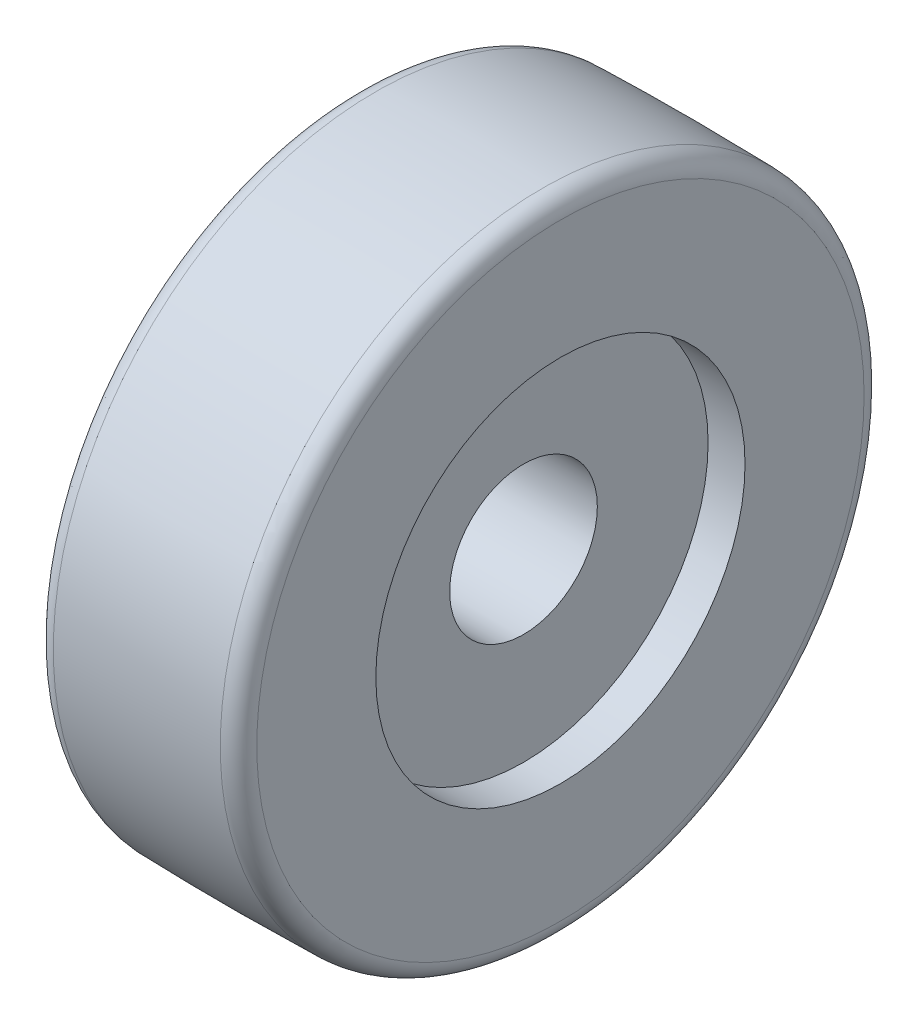
SolidWorks part; units mm, degrees
ref_plane "Front Plane" through (0, 0, 0) normal (0, 0, 1) x (1, 0, 0)
ref_plane "Top Plane" through (0, 0, 0) normal (0, 1, 0) x (1, 0, 0)
ref_plane "Right Plane" through (0, 0, 0) normal (1, 0, 0) x (0, 0, -1)
sketch "Sketch1" plane through (0, 0, 0) normal (0, 0, 1) x (1, 0, 0)
  line L0 (-5.5, 16.4491) -> (-5.5, 10)
  line L1 (-5.5, 10) -> (-3.5, 10)
  line L2 (-3.5, 10) -> (-3.5, 4)
  line L3 (-3.5, 4) -> (3.5, 4)
  line L4 (3.5, 4) -> (3.5, 10)
  line L5 (3.5, 10) -> (5.5, 10)
  line L6 (5.5, 10) -> (5.5, 16.4491)
  line L7 (-5.5, 0) -> (5.5, 0) construction
  arc A0 (-4.5226, 17.4489) -> (-5.5, 16.4491) centre (-4.5, 16.4491) ccw
  arc A1 (5.5, 16.4491) -> (4.5226, 17.4489) centre (4.5, 16.4491) ccw
  arc A2 (4.5226, 17.4489) -> (-4.5226, 17.4489) centre (0, -182.5) ccw
revolve "Revolve1" add sketch "Sketch1" angle 360 about L7
